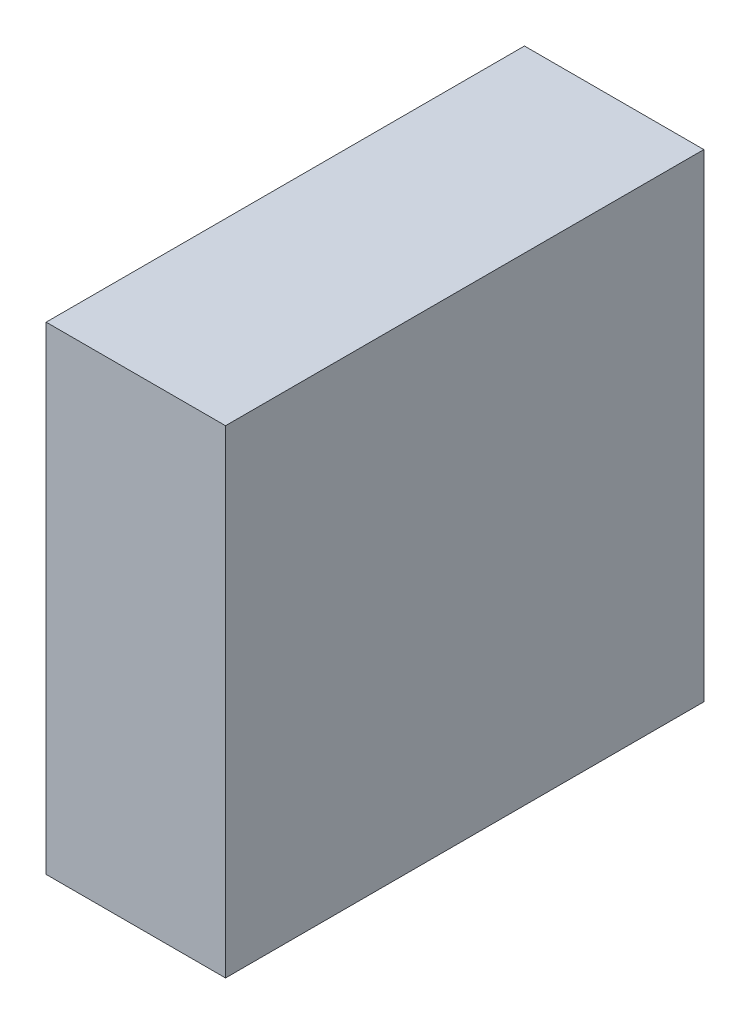
SolidWorks part; units mm, degrees
ref_plane "Front Plane" through (0, 0, 0) normal (0, 0, 1) x (1, 0, 0)
ref_plane "Top Plane" through (0, 0, 0) normal (0, 1, 0) x (1, 0, 0)
ref_plane "Right Plane" through (0, 0, 0) normal (1, 0, 0) x (0, 0, -1)
sketch "Sketch1" plane through (0, 0, 0) normal (0, 1, 0) x (1, 0, 0)
  line L1 (0, 0) -> (9.525, 0)
  line L2 (0, 0) -> (0, 25.4)
  line L3 (0, 25.4) -> (9.525, 25.4)
  line L4 (9.525, 0) -> (9.525, 25.4)
  point P9 (0, 0)
  point P11 (0, 0)
  point P12 (0, 0)
  dimension "D5" = 9.525
  dimension "D4" = 25.4
extrude "Boss-Extrude1" add sketch "Sketch1" along normal blind 25.4
sketch "Sketch4" plane through (0, 0, 0) normal (0, -1, 0) x (1, 0, 0)
  line L0 (9.525, 0) -> (9.525, -25.4) construction
  line L1 (0, 0) -> (9.525, 0) construction
  line L2 (0, 0) -> (0, -25.4) construction
  line L3 (0, -25.4) -> (9.525, -25.4) construction
  line L4 (9.525, 0) -> (9.525, -25.4)
  line L5 (0, 0) -> (9.525, 0)
  line L6 (0, 0) -> (0, -25.4)
  line L7 (0, -25.4) -> (9.525, -25.4)
  circle A0 centre (4.7625, -19.05) radius 1.5875
  circle A1 centre (4.7625, -6.35) radius 1.5875
  point P8 (0, 0)
  point P9 (0, 0)
  point P10 (4.7625, -25.4)
  point P11 (0, 0)
  point P13 (-8.015, -23.4372)
  dimension "D1" = 3.175
  dimension "D2" = 3.175
  dimension "D3" = 12.7
  dimension "D4" = 6.35
extrude "Cut-Extrude1" cut sketch "Sketch4" against normal blind 9.525 contours A0 | A1
